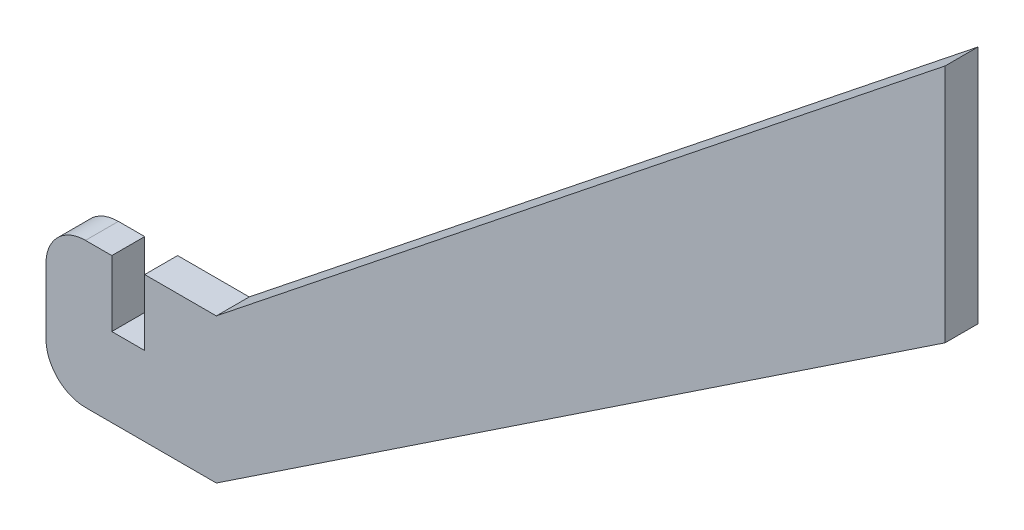
SolidWorks part; units mm, degrees
material "PBT General Purpose"
ref_plane "Front Plane" through (0, 0, 0) normal (0, 0, 1) x (1, 0, 0)
ref_plane "Top Plane" through (0, 0, 0) normal (0, 1, 0) x (1, 0, 0)
ref_plane "Right Plane" through (0, 0, 0) normal (1, 0, 0) x (0, 0, -1)
sketch "frame_outline" plane through (0, 0, 0) normal (0, 0, 1) x (1, 0, 0)
  line L127 (0, 0) -> (0, 1.1)
  line L128 (0, 1.1) -> (0.5, 1.1)
  line L129 (0.5, 1.1) -> (0.5, 0.6)
  line L130 (0.5, 0.6) -> (0.75, 0.6)
  line L131 (0.75, 0.6) -> (0.75, 1.1)
  line L132 (0.75, 1.1) -> (1.2943, 1.1)
  line L139 (1.2943, 0) -> (0, 0)
  line L140 (1.2943, 1.1) -> (6.8322, 5.514)
  line L141 (6.8322, 5.514) -> (6.8322, 3.6918)
  line L142 (6.8322, 3.6918) -> (1.2943, 0)
  dimension "D1" = 0.25
  dimension "D2" = 0.5
  dimension "D3" = 0.6
  dimension "D4" = 0.5
extrude "Boss-Extrude1" add sketch "frame_outline" along normal mid plane 0.25
fillet "Fillet1" radius 0.3 2 edges at (0, 1.1, 0) (0, 0, 0)
equation "\"t\"= 0.25'thickness of the sheets"
equation "\"t_cf\"= 0.115'thickness of single carbon fiber layer"
equation "\"t_kapton\"= 0.025'thickness of single Kapton flex layer"
equation "\"t_fr4\"= 0.1'thickness of FR4 with copper layer"
equation "\"joint_flex\"= 0.1'Width of flextures gap"
equation "\"joint_flex_eff\"= 0.02'Width of flecture after castelation"
equation "\"joint_fold\"= 0.2'Width of folding joints for 90deg fold"
equation "\"gap_tolerance\"= 0.002'Width to have interfecence fit between carbon fiber inserts"
equation "\"assemble_angle\"= 90'Angle of assembly parts"
equation "\"D1@Boss-Extrude1\"=\"t\""
equation "\"link_lift\"= 0.5'Actuation linkage amplification for the lift motion"
equation "\"link_swing\"= 0.45'Actuation linkage amplification for the swing motion"
equation "\"D1@frame_outline\"=\"t\""
